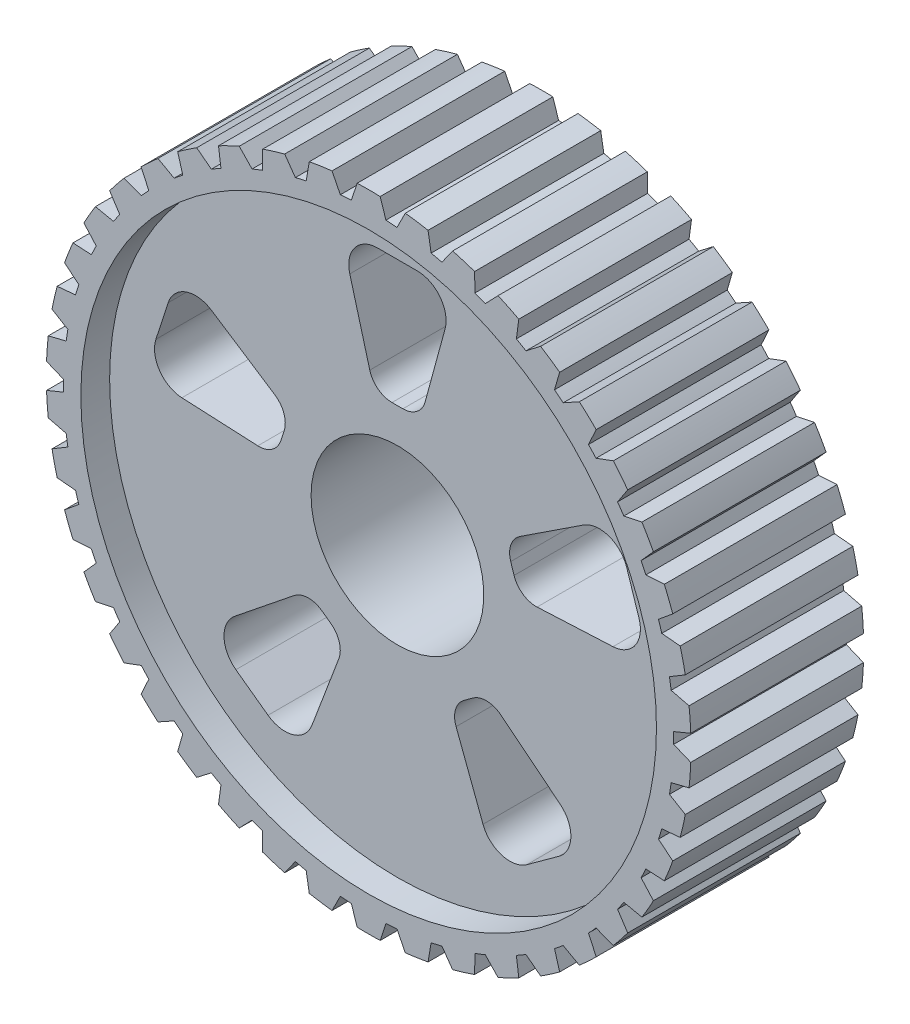
SolidWorks part; units mm, degrees
ref_plane "Спереди" through (0, 0, 0) normal (0, 0, 1) x (1, 0, 0)
ref_plane "Сверху" through (0, 0, 0) normal (0, 1, 0) x (1, 0, 0)
ref_plane "Справа" through (0, 0, 0) normal (1, 0, 0) x (0, 0, -1)
sketch "Эскиз1" plane through (0, 0, 0) normal (0, 0, 1) x (1, 0, 0)
  line L0 (0, 0) -> (0, 56) construction
  line L1 (-2, 55.9643) -> (-3, 52.915)
  line L2 (2, 55.9643) -> (3, 52.915)
  line L3 (6.3634, 55.6373) -> (4.9201, 52.7711)
  line L4 (10.3187, 55.0411) -> (10.8531, 51.8769)
  line L5 (14.5846, 54.0674) -> (12.7303, 51.4484)
  line L6 (18.4069, 52.8884) -> (18.4637, 49.6799)
  line L7 (22.4801, 51.2898) -> (20.2561, 48.9764)
  line L8 (26.0839, 49.5543) -> (25.6619, 46.3731)
  line L9 (29.8733, 47.3665) -> (27.3294, 45.4104)
  line L10 (33.1783, 45.1132) -> (32.2868, 42.0305)
  line L11 (36.5993, 42.3851) -> (33.7922, 40.83)
  line L12 (39.5315, 39.6644) -> (38.1905, 36.7489)
  line L13 (42.5077, 36.4568) -> (39.5002, 35.3375)
  line L14 (45.0016, 33.3295) -> (43.2411, 30.6465)
  line L15 (47.4665, 29.7142) -> (44.3258, 29.0556)
  line L16 (49.4665, 26.2501) -> (47.3258, 23.8594)
  line L17 (51.365, 22.3078) -> (48.1612, 22.1247)
  line L18 (52.8264, 18.5843) -> (50.3532, 16.5394)
  line L19 (54.1161, 14.4031) -> (50.9208, 14.6995)
  line L20 (55.0062, 10.5034) -> (52.2559, 8.8499)
  line L21 (55.6583, 6.1766) -> (52.5429, 6.946)
  line L22 (55.9572, 2.1878) -> (52.9913, 0.9627)
  line L23 (55.9572, -2.1878) -> (52.9913, -0.9627)
  line L24 (55.6583, -6.1766) -> (52.5429, -6.946)
  line L25 (55.0062, -10.5034) -> (52.2559, -8.8499)
  line L26 (54.1161, -14.4031) -> (50.9208, -14.6995)
  line L27 (52.8264, -18.5843) -> (50.3532, -16.5394)
  line L28 (51.365, -22.3078) -> (48.1612, -22.1247)
  line L29 (49.4665, -26.2501) -> (47.3258, -23.8594)
  line L30 (47.4665, -29.7142) -> (44.3258, -29.0556)
  line L31 (45.0016, -33.3295) -> (43.2411, -30.6465)
  line L32 (42.5077, -36.4568) -> (39.5002, -35.3375)
  line L33 (39.5315, -39.6644) -> (38.1905, -36.7489)
  line L34 (36.5993, -42.3851) -> (33.7922, -40.83)
  line L35 (33.1783, -45.1132) -> (32.2868, -42.0305)
  line L36 (29.8733, -47.3665) -> (27.3294, -45.4104)
  line L37 (26.0839, -49.5543) -> (25.6619, -46.3731)
  line L38 (22.4801, -51.2898) -> (20.2561, -48.9764)
  line L39 (18.4069, -52.8884) -> (18.4637, -49.6799)
  line L40 (14.5846, -54.0674) -> (12.7303, -51.4484)
  line L41 (10.3187, -55.0411) -> (10.8531, -51.8769)
  line L42 (6.3634, -55.6373) -> (4.9201, -52.7711)
  line L43 (2, -55.9643) -> (3, -52.915)
  line L44 (-2, -55.9643) -> (-3, -52.915)
  line L45 (-6.3634, -55.6373) -> (-4.9201, -52.7711)
  line L46 (-10.3187, -55.0411) -> (-10.8531, -51.8769)
  line L47 (-14.5846, -54.0674) -> (-12.7303, -51.4484)
  line L48 (-18.4069, -52.8884) -> (-18.4637, -49.6799)
  line L49 (-22.4801, -51.2898) -> (-20.2561, -48.9764)
  line L50 (-26.0839, -49.5543) -> (-25.6619, -46.3731)
  line L51 (-29.8733, -47.3665) -> (-27.3294, -45.4104)
  line L52 (-33.1783, -45.1132) -> (-32.2868, -42.0305)
  line L53 (-36.5993, -42.3851) -> (-33.7922, -40.83)
  line L54 (-39.5315, -39.6644) -> (-38.1905, -36.7489)
  line L55 (-42.5077, -36.4568) -> (-39.5002, -35.3375)
  line L56 (-45.0016, -33.3295) -> (-43.2411, -30.6465)
  line L57 (-47.4665, -29.7142) -> (-44.3258, -29.0556)
  line L58 (-49.4665, -26.2501) -> (-47.3258, -23.8594)
  line L59 (-51.365, -22.3078) -> (-48.1612, -22.1247)
  line L60 (-52.8264, -18.5843) -> (-50.3532, -16.5394)
  line L61 (-54.1161, -14.4031) -> (-50.9208, -14.6995)
  line L62 (-55.0062, -10.5034) -> (-52.2559, -8.8499)
  line L63 (-55.6583, -6.1766) -> (-52.5429, -6.946)
  line L64 (-55.9572, -2.1878) -> (-52.9913, -0.9627)
  line L65 (-55.9572, 2.1878) -> (-52.9913, 0.9627)
  line L66 (-55.6583, 6.1766) -> (-52.5429, 6.946)
  line L67 (-55.0062, 10.5034) -> (-52.2559, 8.8499)
  line L68 (-54.1161, 14.4031) -> (-50.9208, 14.6995)
  line L69 (-52.8264, 18.5843) -> (-50.3532, 16.5394)
  line L70 (-51.365, 22.3078) -> (-48.1612, 22.1247)
  line L71 (-49.4665, 26.2501) -> (-47.3258, 23.8594)
  line L72 (-47.4665, 29.7142) -> (-44.3258, 29.0556)
  line L73 (-45.0016, 33.3295) -> (-43.2411, 30.6465)
  line L74 (-42.5077, 36.4568) -> (-39.5002, 35.3375)
  line L75 (-39.5315, 39.6644) -> (-38.1905, 36.7489)
  line L76 (-36.5993, 42.3851) -> (-33.7922, 40.83)
  line L77 (-33.1783, 45.1132) -> (-32.2868, 42.0305)
  line L78 (-29.8733, 47.3665) -> (-27.3294, 45.4104)
  line L79 (-26.0839, 49.5543) -> (-25.6619, 46.3731)
  line L80 (-22.4801, 51.2898) -> (-20.2561, 48.9764)
  line L81 (-18.4069, 52.8884) -> (-18.4637, 49.6799)
  line L82 (-14.5846, 54.0674) -> (-12.7303, 51.4484)
  line L83 (-10.3187, 55.0411) -> (-10.8531, 51.8769)
  line L84 (-6.3634, 55.6373) -> (-4.9201, 52.7711)
  arc A0 (2, 55.9643) -> (-2, 55.9643) centre (0, 0) ccw
  arc A1 (-3, 52.915) -> (-3.965, 52.8515) centre (0, 0) ccw
  arc A2 (3, 52.915) -> (3.965, 52.8515) centre (0, 0) cw
  arc A3 (4.9201, 52.7711) -> (3.9564, 52.8521) centre (0, 0) ccw
  arc A4 (10.3187, 55.0411) -> (6.3634, 55.6373) centre (0, 0) ccw
  arc A5 (10.8531, 51.8769) -> (11.7978, 51.6702) centre (0, 0) cw
  arc A6 (12.7303, 51.4484) -> (11.7894, 51.6721) centre (0, 0) ccw
  arc A7 (18.4069, 52.8884) -> (14.5846, 54.0674) centre (0, 0) ccw
  arc A8 (18.4637, 49.6799) -> (19.3671, 49.3347) centre (0, 0) cw
  arc A9 (20.2561, 48.9764) -> (19.3591, 49.3379) centre (0, 0) ccw
  arc A10 (26.0839, 49.5543) -> (22.4801, 51.2898) centre (0, 0) ccw
  arc A11 (25.6619, 46.3731) -> (26.5037, 45.8972) centre (0, 0) cw
  arc A12 (27.3294, 45.4104) -> (26.4963, 45.9015) centre (0, 0) ccw
  arc A13 (33.1783, 45.1132) -> (29.8733, 47.3665) centre (0, 0) ccw
  arc A14 (32.2868, 42.0305) -> (33.0483, 41.4344) centre (0, 0) cw
  arc A15 (33.7922, 40.83) -> (33.0416, 41.4398) centre (0, 0) ccw
  arc A16 (39.5315, 39.6644) -> (36.5993, 42.3851) centre (0, 0) ccw
  arc A17 (38.1905, 36.7489) -> (38.8547, 36.046) centre (0, 0) cw
  arc A18 (39.5002, 35.3375) -> (38.8488, 36.0523) centre (0, 0) ccw
  arc A19 (45.0016, 33.3295) -> (42.5077, 36.4568) centre (0, 0) ccw
  arc A20 (43.2411, 30.6465) -> (43.7931, 29.8524) centre (0, 0) cw
  arc A21 (44.3258, 29.0556) -> (43.7882, 29.8595) centre (0, 0) ccw
  arc A22 (49.4665, 26.2501) -> (47.4665, 29.7142) centre (0, 0) ccw
  arc A23 (47.3258, 23.8594) -> (47.7532, 22.9919) centre (0, 0) cw
  arc A24 (48.1612, 22.1247) -> (47.7495, 22.9997) centre (0, 0) ccw
  arc A25 (52.8264, 18.5843) -> (51.365, 22.3078) centre (0, 0) ccw
  arc A26 (50.3532, 16.5394) -> (50.6466, 15.6179) centre (0, 0) cw
  arc A27 (50.9208, 14.6995) -> (50.6441, 15.6261) centre (0, 0) ccw
  arc A28 (55.0062, 10.5034) -> (54.1161, 14.4031) centre (0, 0) ccw
  arc A29 (52.2559, 8.8499) -> (52.4087, 7.895) centre (0, 0) cw
  arc A30 (52.5429, 6.946) -> (52.4074, 7.9035) centre (0, 0) ccw
  arc A31 (55.9572, 2.1878) -> (55.6583, 6.1766) centre (0, 0) ccw
  arc A32 (52.9913, 0.9627) -> (53, -0.0043) centre (0, 0) cw
  arc A33 (52.9913, -0.9627) -> (53, 0.0043) centre (0, 0) ccw
  arc A34 (55.6583, -6.1766) -> (55.9572, -2.1878) centre (0, 0) ccw
  arc A35 (52.5429, -6.946) -> (52.4074, -7.9035) centre (0, 0) cw
  arc A36 (52.2559, -8.8499) -> (52.4087, -7.895) centre (0, 0) ccw
  arc A37 (54.1161, -14.4031) -> (55.0062, -10.5034) centre (0, 0) ccw
  arc A38 (50.9208, -14.6995) -> (50.6441, -15.6261) centre (0, 0) cw
  arc A39 (50.3532, -16.5394) -> (50.6466, -15.6179) centre (0, 0) ccw
  arc A40 (51.365, -22.3078) -> (52.8264, -18.5843) centre (0, 0) ccw
  arc A41 (48.1612, -22.1247) -> (47.7495, -22.9997) centre (0, 0) cw
  arc A42 (47.3258, -23.8594) -> (47.7532, -22.9919) centre (0, 0) ccw
  arc A43 (47.4665, -29.7142) -> (49.4665, -26.2501) centre (0, 0) ccw
  arc A44 (44.3258, -29.0556) -> (43.7882, -29.8595) centre (0, 0) cw
  arc A45 (43.2411, -30.6465) -> (43.7931, -29.8524) centre (0, 0) ccw
  arc A46 (42.5077, -36.4568) -> (45.0016, -33.3295) centre (0, 0) ccw
  arc A47 (39.5002, -35.3375) -> (38.8488, -36.0523) centre (0, 0) cw
  arc A48 (38.1905, -36.7489) -> (38.8547, -36.046) centre (0, 0) ccw
  arc A49 (36.5993, -42.3851) -> (39.5315, -39.6644) centre (0, 0) ccw
  arc A50 (33.7922, -40.83) -> (33.0416, -41.4398) centre (0, 0) cw
  arc A51 (32.2868, -42.0305) -> (33.0483, -41.4344) centre (0, 0) ccw
  arc A52 (29.8733, -47.3665) -> (33.1783, -45.1132) centre (0, 0) ccw
  arc A53 (27.3294, -45.4104) -> (26.4963, -45.9015) centre (0, 0) cw
  arc A54 (25.6619, -46.3731) -> (26.5037, -45.8972) centre (0, 0) ccw
  arc A55 (22.4801, -51.2898) -> (26.0839, -49.5543) centre (0, 0) ccw
  arc A56 (20.2561, -48.9764) -> (19.3591, -49.3379) centre (0, 0) cw
  arc A57 (18.4637, -49.6799) -> (19.3671, -49.3347) centre (0, 0) ccw
  arc A58 (14.5846, -54.0674) -> (18.4069, -52.8884) centre (0, 0) ccw
  arc A59 (12.7303, -51.4484) -> (11.7894, -51.6721) centre (0, 0) cw
  arc A60 (10.8531, -51.8769) -> (11.7978, -51.6702) centre (0, 0) ccw
  arc A61 (6.3634, -55.6373) -> (10.3187, -55.0411) centre (0, 0) ccw
  arc A62 (4.9201, -52.7711) -> (3.9564, -52.8521) centre (0, 0) cw
  arc A63 (3, -52.915) -> (3.965, -52.8515) centre (0, 0) ccw
  arc A64 (-2, -55.9643) -> (2, -55.9643) centre (0, 0) ccw
  arc A65 (-3, -52.915) -> (-3.965, -52.8515) centre (0, 0) cw
  arc A66 (-4.9201, -52.7711) -> (-3.9564, -52.8521) centre (0, 0) ccw
  arc A67 (-10.3187, -55.0411) -> (-6.3634, -55.6373) centre (0, 0) ccw
  arc A68 (-10.8531, -51.8769) -> (-11.7978, -51.6702) centre (0, 0) cw
  arc A69 (-12.7303, -51.4484) -> (-11.7894, -51.6721) centre (0, 0) ccw
  arc A70 (-18.4069, -52.8884) -> (-14.5846, -54.0674) centre (0, 0) ccw
  arc A71 (-18.4637, -49.6799) -> (-19.3671, -49.3347) centre (0, 0) cw
  arc A72 (-20.2561, -48.9764) -> (-19.3591, -49.3379) centre (0, 0) ccw
  arc A73 (-26.0839, -49.5543) -> (-22.4801, -51.2898) centre (0, 0) ccw
  arc A74 (-25.6619, -46.3731) -> (-26.5037, -45.8972) centre (0, 0) cw
  arc A75 (-27.3294, -45.4104) -> (-26.4963, -45.9015) centre (0, 0) ccw
  arc A76 (-33.1783, -45.1132) -> (-29.8733, -47.3665) centre (0, 0) ccw
  arc A77 (-32.2868, -42.0305) -> (-33.0483, -41.4344) centre (0, 0) cw
  arc A78 (-33.7922, -40.83) -> (-33.0416, -41.4398) centre (0, 0) ccw
  arc A79 (-39.5315, -39.6644) -> (-36.5993, -42.3851) centre (0, 0) ccw
  arc A80 (-38.1905, -36.7489) -> (-38.8547, -36.046) centre (0, 0) cw
  arc A81 (-39.5002, -35.3375) -> (-38.8488, -36.0523) centre (0, 0) ccw
  arc A82 (-45.0016, -33.3295) -> (-42.5077, -36.4568) centre (0, 0) ccw
  arc A83 (-43.2411, -30.6465) -> (-43.7931, -29.8524) centre (0, 0) cw
  arc A84 (-44.3258, -29.0556) -> (-43.7882, -29.8595) centre (0, 0) ccw
  arc A85 (-49.4665, -26.2501) -> (-47.4665, -29.7142) centre (0, 0) ccw
  arc A86 (-47.3258, -23.8594) -> (-47.7532, -22.9919) centre (0, 0) cw
  arc A87 (-48.1612, -22.1247) -> (-47.7495, -22.9997) centre (0, 0) ccw
  arc A88 (-52.8264, -18.5843) -> (-51.365, -22.3078) centre (0, 0) ccw
  arc A89 (-50.3532, -16.5394) -> (-50.6466, -15.6179) centre (0, 0) cw
  arc A90 (-50.9208, -14.6995) -> (-50.6441, -15.6261) centre (0, 0) ccw
  arc A91 (-55.0062, -10.5034) -> (-54.1161, -14.4031) centre (0, 0) ccw
  arc A92 (-52.2559, -8.8499) -> (-52.4087, -7.895) centre (0, 0) cw
  arc A93 (-52.5429, -6.946) -> (-52.4074, -7.9035) centre (0, 0) ccw
  arc A94 (-55.9572, -2.1878) -> (-55.6583, -6.1766) centre (0, 0) ccw
  arc A95 (-52.9913, -0.9627) -> (-53, 0.0043) centre (0, 0) cw
  arc A96 (-52.9913, 0.9627) -> (-53, -0.0043) centre (0, 0) ccw
  arc A97 (-55.6583, 6.1766) -> (-55.9572, 2.1878) centre (0, 0) ccw
  arc A98 (-52.5429, 6.946) -> (-52.4074, 7.9035) centre (0, 0) cw
  arc A99 (-52.2559, 8.8499) -> (-52.4087, 7.895) centre (0, 0) ccw
  arc A100 (-54.1161, 14.4031) -> (-55.0062, 10.5034) centre (0, 0) ccw
  arc A101 (-50.9208, 14.6995) -> (-50.6441, 15.6261) centre (0, 0) cw
  arc A102 (-50.3532, 16.5394) -> (-50.6466, 15.6179) centre (0, 0) ccw
  arc A103 (-51.365, 22.3078) -> (-52.8264, 18.5843) centre (0, 0) ccw
  arc A104 (-48.1612, 22.1247) -> (-47.7495, 22.9997) centre (0, 0) cw
  arc A105 (-47.3258, 23.8594) -> (-47.7532, 22.9919) centre (0, 0) ccw
  arc A106 (-47.4665, 29.7142) -> (-49.4665, 26.2501) centre (0, 0) ccw
  arc A107 (-44.3258, 29.0556) -> (-43.7882, 29.8595) centre (0, 0) cw
  arc A108 (-43.2411, 30.6465) -> (-43.7931, 29.8524) centre (0, 0) ccw
  arc A109 (-42.5077, 36.4568) -> (-45.0016, 33.3295) centre (0, 0) ccw
  arc A110 (-39.5002, 35.3375) -> (-38.8488, 36.0523) centre (0, 0) cw
  arc A111 (-38.1905, 36.7489) -> (-38.8547, 36.046) centre (0, 0) ccw
  arc A112 (-36.5993, 42.3851) -> (-39.5315, 39.6644) centre (0, 0) ccw
  arc A113 (-33.7922, 40.83) -> (-33.0416, 41.4398) centre (0, 0) cw
  arc A114 (-32.2868, 42.0305) -> (-33.0483, 41.4344) centre (0, 0) ccw
  arc A115 (-29.8733, 47.3665) -> (-33.1783, 45.1132) centre (0, 0) ccw
  arc A116 (-27.3294, 45.4104) -> (-26.4963, 45.9015) centre (0, 0) cw
  arc A117 (-25.6619, 46.3731) -> (-26.5037, 45.8972) centre (0, 0) ccw
  arc A118 (-22.4801, 51.2898) -> (-26.0839, 49.5543) centre (0, 0) ccw
  arc A119 (-20.2561, 48.9764) -> (-19.3591, 49.3379) centre (0, 0) cw
  arc A120 (-18.4637, 49.6799) -> (-19.3671, 49.3347) centre (0, 0) ccw
  arc A121 (-14.5846, 54.0674) -> (-18.4069, 52.8884) centre (0, 0) ccw
  arc A122 (-12.7303, 51.4484) -> (-11.7894, 51.6721) centre (0, 0) cw
  arc A123 (-10.8531, 51.8769) -> (-11.7978, 51.6702) centre (0, 0) ccw
  arc A124 (-6.3634, 55.6373) -> (-10.3187, 55.0411) centre (0, 0) ccw
  arc A125 (-4.9201, 52.7711) -> (-3.9564, 52.8521) centre (0, 0) cw
  circle A126 centre (0, 0) radius 50
  point P258 (0, 0)
  dimension "D1" = 56
  dimension "D3" = 53
  dimension "D7" = 100
  dimension "D2" = 2
  dimension "D4" = 3
  dimension "D5" = 3.965
  dimension "D6" = 42
extrude "Бобышка-Вытянуть1" add sketch "Эскиз1" along normal mid plane 30
sketch "Эскиз2" plane through (0, 0, -15) normal (0, 0, -1) x (-1, 0, 0)
  line L0 (0, 0) -> (0, 41.684) construction
  line L1 (3.4537, 43) -> (-3.4537, 43)
  line L2 (-8.2776, 36.6844) -> (-4.8039, 23.9475)
  line L3 (-0.9448, 21) -> (0.9448, 21)
  line L4 (8.2776, 36.6844) -> (4.8039, 23.9475)
  line L5 (41.9627, 10.003) -> (39.8282, 16.5724)
  line L6 (32.331, 19.2085) -> (21.291, 11.9689)
  line L7 (37.4469, 3.4637) -> (24.2599, 2.8314)
  line L8 (19.6802, 7.3879) -> (20.2642, 5.5908)
  line L9 (22.4806, -36.8178) -> (28.0689, -32.7577)
  line L10 (28.2592, -24.8129) -> (17.9624, -16.5503)
  line L11 (14.8659, -34.5437) -> (10.1896, -22.1976)
  line L12 (13.1079, -16.434) -> (11.5791, -17.5447)
  line L13 (-28.0689, -32.7577) -> (-22.4806, -36.8178)
  line L14 (-14.8659, -34.5437) -> (-10.1896, -22.1976)
  line L15 (-28.2592, -24.8129) -> (-17.9624, -16.5503)
  line L16 (-11.5791, -17.5447) -> (-13.1079, -16.434)
  line L17 (-39.8282, 16.5724) -> (-41.9627, 10.003)
  line L18 (-37.4469, 3.4637) -> (-24.2599, 2.8314)
  line L19 (-32.331, 19.2085) -> (-21.291, 11.9689)
  line L20 (-20.2642, 5.5908) -> (-19.6802, 7.3879)
  circle A0 centre (0, 0) radius 15
  arc A1 (-3.4537, 43) -> (-8.2776, 36.6844) centre (-3.4537, 38) ccw
  arc A2 (-4.8039, 23.9475) -> (-0.9448, 21) centre (-0.9448, 25) ccw
  arc A3 (4.8039, 23.9475) -> (0.9448, 21) centre (0.9448, 25) cw
  arc A4 (3.4537, 43) -> (8.2776, 36.6844) centre (3.4537, 38) cw
  arc A5 (39.8282, 16.5724) -> (32.331, 19.2085) centre (35.0729, 15.0274) ccw
  arc A6 (21.291, 11.9689) -> (19.6802, 7.3879) centre (23.4844, 8.624) ccw
  arc A7 (24.2599, 2.8314) -> (20.2642, 5.5908) centre (24.0684, 6.8269) cw
  arc A8 (41.9627, 10.003) -> (37.4469, 3.4637) centre (37.2074, 8.4579) cw
  arc A9 (28.0689, -32.7577) -> (28.2592, -24.8129) centre (25.13, -28.7126) ccw
  arc A10 (17.9624, -16.5503) -> (13.1079, -16.434) centre (15.459, -19.6701) ccw
  arc A11 (10.1896, -22.1976) -> (11.5791, -17.5447) centre (13.9303, -20.7808) cw
  arc A12 (22.4806, -36.8178) -> (14.8659, -34.5437) centre (19.5417, -32.7727) cw
  arc A13 (-22.4806, -36.8178) -> (-14.8659, -34.5437) centre (-19.5417, -32.7727) ccw
  arc A14 (-10.1896, -22.1976) -> (-11.5791, -17.5447) centre (-13.9303, -20.7808) ccw
  arc A15 (-17.9624, -16.5503) -> (-13.1079, -16.434) centre (-15.459, -19.6701) cw
  arc A16 (-28.0689, -32.7577) -> (-28.2592, -24.8129) centre (-25.13, -28.7126) cw
  arc A17 (-41.9627, 10.003) -> (-37.4469, 3.4637) centre (-37.2074, 8.4579) ccw
  arc A18 (-24.2599, 2.8314) -> (-20.2642, 5.5908) centre (-24.0684, 6.8269) ccw
  arc A19 (-21.291, 11.9689) -> (-19.6802, 7.3879) centre (-23.4844, 8.624) cw
  arc A20 (-39.8282, 16.5724) -> (-32.331, 19.2085) centre (-35.0729, 15.0274) cw
  circle A21 centre (0, 0) radius 50
  point P10 (-10, 43)
  point P14 (-4, 21)
  point P16 (0, 21)
  point P21 (0, 43)
  point P34 (40.8954, 13.2877)
  point P47 (25.2748, -34.7877)
  point P60 (-25.2748, -34.7877)
  point P73 (-40.8954, 13.2877)
  point P74 (0, 0)
  dimension "D1" = 30
  dimension "D6" = 5
  dimension "D7" = 4
  dimension "D9" = 100
  dimension "D2" = 21
  dimension "D3" = 22
  dimension "D4" = 10
  dimension "D5" = 4
  dimension "D8" = 5
extrude "Бобышка-Вытянуть2" add sketch "Эскиз2" against normal blind 25
